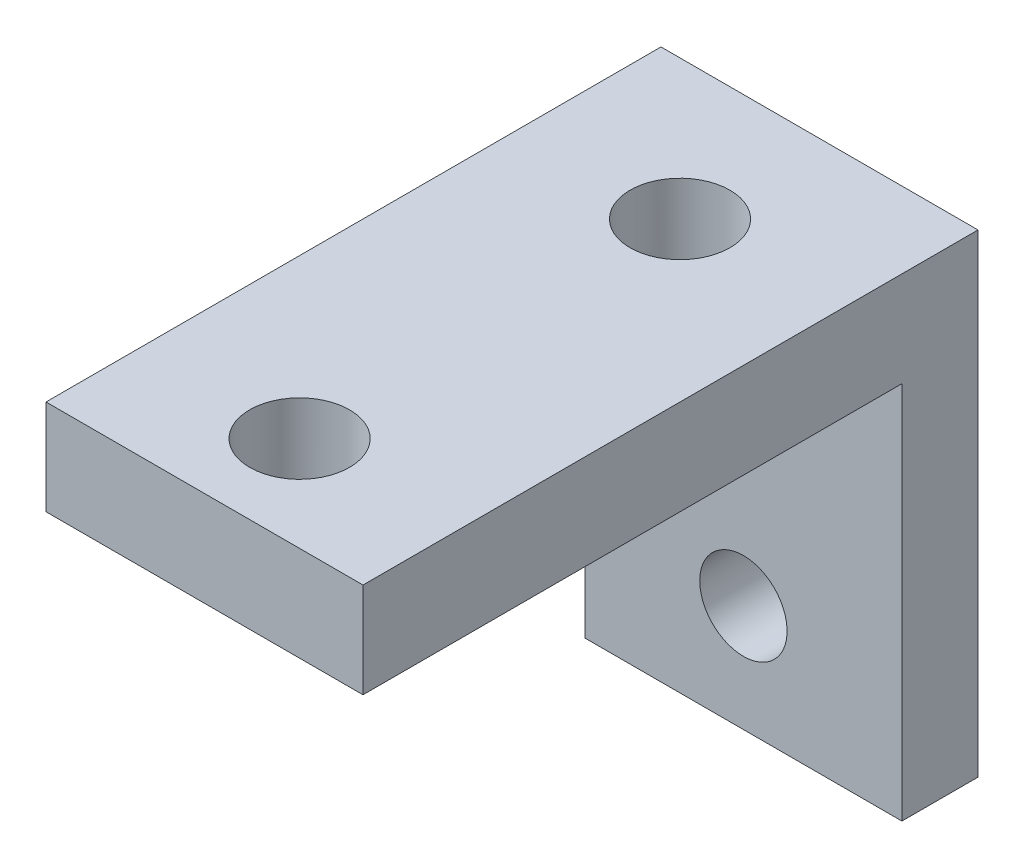
SolidWorks part; units mm, degrees
ref_plane "Front Plane" through (0, 0, 0) normal (0, 0, 1) x (1, 0, 0)
ref_plane "Top Plane" through (0, 0, 0) normal (0, 1, 0) x (1, 0, 0)
ref_plane "Right Plane" through (0, 0, 0) normal (1, 0, 0) x (0, 0, -1)
sketch "Sketch1" plane through (0, 0, 0) normal (0, 0, 1) x (1, 0, 0)
  line L0 (0, 9.493) -> (0, -9.493) construction
  line L1 (-6.35, -9.493) -> (6.35, -9.493)
  line L2 (-6.35, -9.493) -> (-6.35, 9.493)
  line L3 (-6.35, 9.493) -> (6.35, 9.493)
  line L4 (6.35, -9.493) -> (6.35, 9.493)
  line L5 (-6.35, -9.493) -> (6.35, 9.493) construction
  line L6 (-6.35, 9.493) -> (6.35, -9.493) construction
  circle A0 centre (0, -5.203) radius 1.75
  point P0 (0, 0)
  point P11 (0, -6.953)
  dimension "D3" = 3.5
  dimension "D1" = 18.986
  dimension "D2" = 12.7
  dimension "D4" = 2.54
extrude "Boss-Extrude1" add sketch "Sketch1" along normal blind 3.048
sketch "Sketch3" plane through (6.35, 0, 0) normal (1, 0, 0) x (0, 0, -1)
  line L1 (-3.048, 9.493) -> (-24.638, 9.493)
  line L2 (-3.048, 9.493) -> (-3.048, 5.683)
  line L3 (-3.048, 5.683) -> (-24.638, 5.683)
  line L4 (-24.638, 9.493) -> (-24.638, 5.683)
  dimension "D1" = 3.81
  dimension "D2" = 21.59
extrude "Boss-Extrude2" add sketch "Sketch3" against normal through all
sketch "Sketch4" plane through (0, 9.493, 0) normal (0, 1, 0) x (1, 0, 0)
  line L0 (-6.35, -24.638) -> (6.35, -24.638) construction
  line L1 (0, 0) -> (0, -24.638) construction
  line L2 (6.35, 0) -> (-6.35, 0) construction
  line L6 (-6.35, -13.208) -> (6.35, -13.208) construction
  circle A0 centre (0, -20.828) radius 2
  circle A1 centre (0, -5.588) radius 2
  point P18 (6.35, -2.8217)
  dimension "D2" = 4
  dimension "D1" = 3.81
  dimension "D3" = 11.43
extrude "Cut-Extrude1" cut sketch "Sketch4" against normal through all
